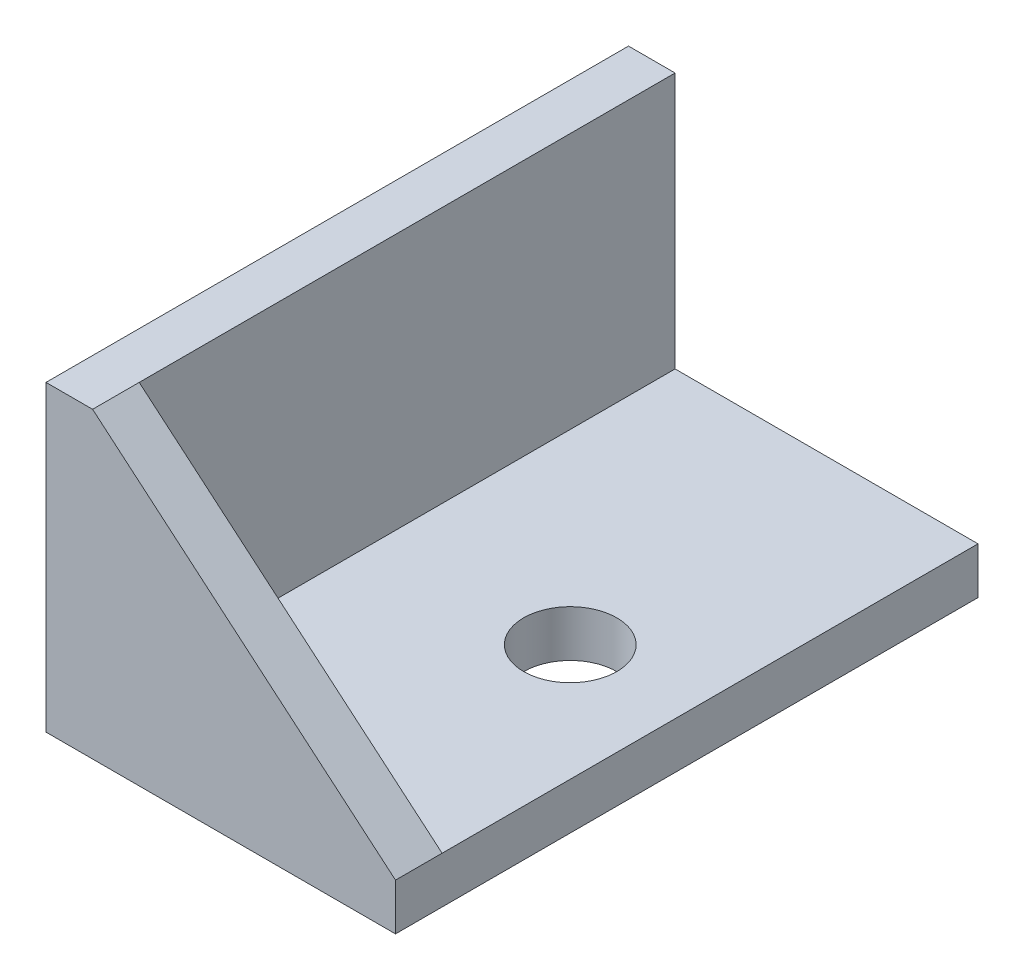
SolidWorks part; units mm, degrees
ref_plane "Płaszczyzna przednia" through (0, 0, 0) normal (0, 0, 1) x (1, 0, 0)
ref_plane "Płaszczyzna górna" through (0, 0, 0) normal (0, 1, 0) x (1, 0, 0)
ref_plane "Płaszczyzna prawa" through (0, 0, 0) normal (1, 0, 0) x (0, 0, -1)
sketch "Szkic2" plane through (0, 0, 0) normal (0, 0, 1) x (1, 0, 0)
  line L0 (0, 0) -> (0, 65)
  line L1 (0, 65) -> (10, 65)
  line L2 (10, 65) -> (10, 10)
  line L3 (10, 10) -> (75, 10)
  line L4 (75, 10) -> (75, 0)
  line L5 (75, 0) -> (0, 0)
  dimension "D1" = 55
  dimension "D2" = 10
  dimension "D3" = 10
  dimension "D4" = 75
extrude "Dodanie-wyciągnięcie1" add sketch "Szkic2" against normal blind 125
sketch "Szkic3" plane through (0, 0, 0) normal (0, 0, 1) x (1, 0, 0)
  line L0 (10, 65) -> (75, 10)
  line L1 (75, 10) -> (10, 10)
  line L2 (10, 10) -> (10, 65)
extrude "Dodanie-wyciągnięcie3" add sketch "Szkic3" against normal blind 10
sketch "Szkic4" plane through (0, 10, 0) normal (0, 1, 0) x (1, 0, 0)
  line L0 (75, 125) -> (75, 10) construction
  line L1 (75, 125) -> (10, 125) construction
  circle A0 centre (50, 62.5) radius 10
  dimension "D2" = 20
  dimension "D1" = 25
  dimension "D3" = 62.5
extrude "Wytnij-wyciągnięcie1" cut sketch "Szkic4" against normal blind 10
